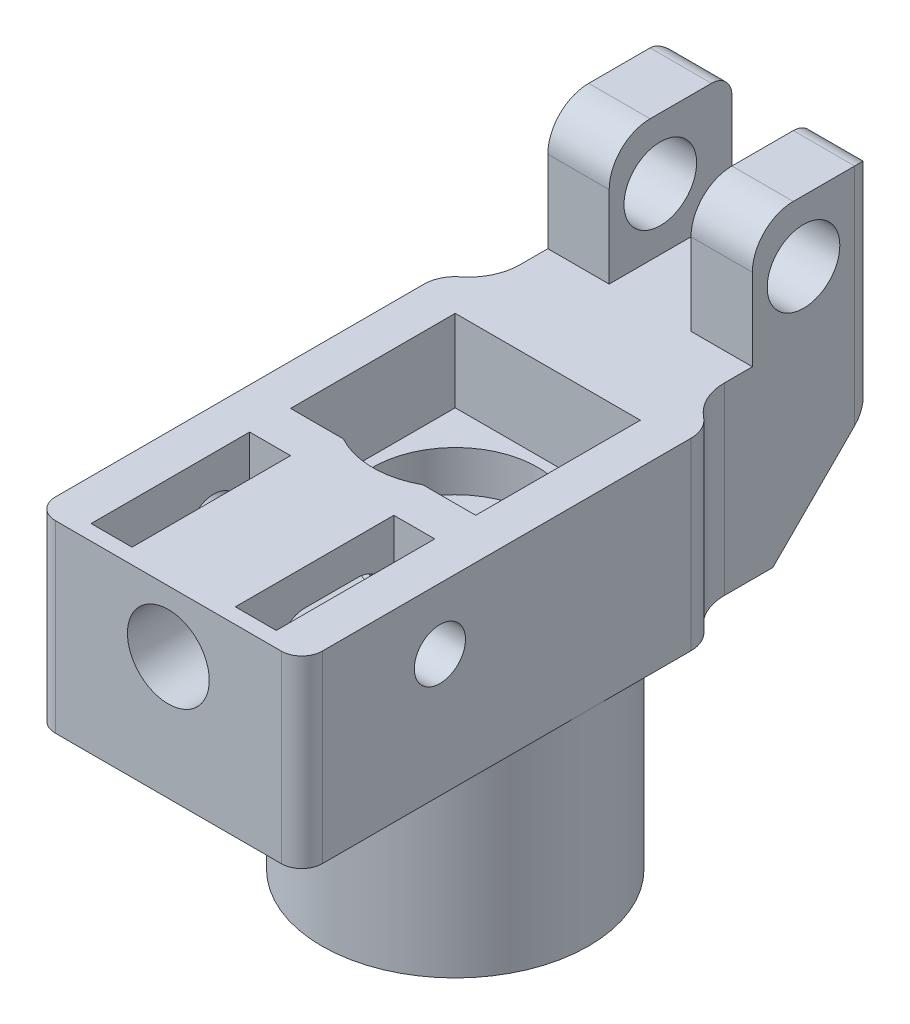
SolidWorks part; units mm, degrees
material "PF"
ref_plane "Front Plane" through (0, 0, 0) normal (0, 0, 1) x (1, 0, 0)
ref_plane "Top Plane" through (0, 0, 0) normal (0, 1, 0) x (1, 0, 0)
ref_plane "Right Plane" through (0, 0, 0) normal (1, 0, 0) x (0, 0, -1)
sketch "Sketch1" plane through (0, 0, 0) normal (0, 1, 0) x (1, 0, 0)
  circle A0 centre (0, 0) radius 8.05
  circle A1 centre (0, 0) radius 13.05
  dimension "D1" = 16.1
  dimension "D2" = 5
extrude "Boss-Extrude1" add sketch "Sketch1" along normal blind 20
sketch "Sketch2" plane through (0, 20, 0) normal (0, 1, 0) x (1, 0, 0)
  line L2 (-13.05, -13.05) -> (-13.05, 10)
  line L3 (-10, 13.05) -> (10, 13.05)
  line L4 (13.05, -13.05) -> (13.05, 10)
  line L6 (-13.05, -13.05) -> (-13.05, -28.05)
  line L7 (-13.05, -28.05) -> (13.05, -28.05)
  line L8 (13.05, -13.05) -> (13.05, -28.05)
  circle A0 centre (0, 0) radius 8.05
  arc A1 (10, 13.05) -> (13.05, 10) centre (10, 10) cw
  arc A2 (-13.05, 10) -> (-10, 13.05) centre (-10, 10) cw
  point P0 (0, 0)
  dimension "D2" = 3.05
  dimension "D1" = 15
extrude "Boss-Extrude2" add sketch "Sketch2" along normal blind 10
sketch "Sketch3" plane through (0, 30, 0) normal (0, 1, 0) x (1, 0, 0)
  line L5 (9.05, -11.05) -> (-9.05, -11.05)
  line L6 (-9.05, -11.05) -> (-9.05, -24.05)
  line L8 (-9.05, 9.05) -> (-9.05, -24.05)
  line L9 (-9.05, -24.05) -> (9.05, -24.05)
  line L10 (9.05, -24.05) -> (9.05, 9.05)
  line L11 (9.05, 9.05) -> (-9.05, 9.05)
  line L13 (-9.05, -24.05) -> (9.05, -24.05)
  line L14 (9.05, -24.05) -> (9.05, -11.05)
  dimension "D1" = 4
extrude "Cut-Extrude1" cut sketch "Sketch3" against normal blind 4
sketch "Sketch4" plane through (0, 30, 0) normal (0, 1, 0) x (1, 0, 0)
  line L8 (-9.05, 9.05) -> (-9.05, -24.05)
  line L9 (-9.05, -24.05) -> (9.05, -24.05)
  line L10 (9.05, -24.05) -> (9.05, 9.05)
  line L11 (9.05, 9.05) -> (-9.05, 9.05)
  line L12 (-9.05, 9.05) -> (-9.05, -7.05)
  line L13 (-9.05, -24.05) -> (9.05, -24.05)
  line L14 (9.05, -24.05) -> (9.05, -11.05)
  line L15 (9.05, 9.05) -> (-9.05, 9.05)
  line L25 (-9.05, -11.05) -> (9.05, -11.05)
  line L26 (-9.05, -7.05) -> (-3.8859, -7.05)
  line L27 (3.8859, -7.05) -> (9.05, -7.05)
  line L28 (-9.05, -7.05) -> (9.05, -7.05) construction
  line L29 (-13.05, -28.05) -> (13.05, -28.05)
  line L30 (13.05, -28.05) -> (13.05, 10)
  line L31 (10, 13.05) -> (-10, 13.05)
  line L32 (-13.05, 10) -> (-13.05, -28.05)
  line L33 (-13.05, -28.05) -> (13.05, -28.05)
  line L34 (13.05, -28.05) -> (13.05, 10)
  line L35 (10, 13.05) -> (-10, 13.05)
  line L36 (-13.05, 10) -> (-13.05, -28.05)
  line L37 (-9.05, -11.05) -> (-9.05, -24.05)
  line L38 (9.05, -7.05) -> (9.05, 9.05)
  arc A10 (-3.8859, -7.05) -> (3.8859, -7.05) centre (0, 0) ccw
  arc A12 (13.05, 10) -> (10, 13.05) centre (10, 10) ccw
  arc A13 (-10, 13.05) -> (-13.05, 10) centre (-10, 10) ccw
  arc A14 (13.05, 10) -> (10, 13.05) centre (10, 10) ccw
  arc A15 (-10, 13.05) -> (-13.05, 10) centre (-10, 10) ccw
  dimension "D1" = 4
  dimension "D2" = 0
  dimension "D3" = 4
extrude "Boss-Extrude3" add sketch "Sketch4" along normal blind 8
ref_plane "Plane1" through (0, 20, 0) normal (0, 1, 0) x (1, 0, 0)
sketch "Sketch5" plane through (0, 20, 0) normal (0, 1, 0) x (1, 0, 0)
  circle A0 centre (0, 0) radius 4
  circle A1 centre (0, 0) radius 8.05
  dimension "D1" = 8
extrude "Boss-Extrude4" add sketch "Sketch5" along normal blind 6
sketch "Sketch10" plane through (0, 26, 0) normal (0, 1, 0) x (1, 0, 0)
  line L0 (-9.05, -24.05) -> (9.05, -24.05) construction
  line L1 (-5.05, -24.05) -> (5.05, -24.05)
  line L2 (-5.05, -24.05) -> (-5.05, -11.05)
  line L3 (-5.05, -11.05) -> (5.05, -11.05)
  line L4 (5.05, -24.05) -> (5.05, -11.05)
  line L5 (-9.05, -11.05) -> (-9.05, -24.05) construction
  line L6 (9.05, -24.05) -> (9.05, -11.05) construction
  line L7 (9.05, -11.05) -> (-9.05, -11.05) construction
  dimension "D1" = 4
  dimension "D2" = 4
  dimension "D3" = 0
extrude "Boss-Extrude7" add sketch "Sketch10" along normal up to surface (12 mm away) up to face at (0, 38, 1.4561)
sketch "Sketch6" plane through (0, 0, 28.05) normal (0, 0, 1) x (1, 0, 0)
  line L0 (-13.05, 38) -> (13.05, 38) construction
  circle A0 centre (0, 32) radius 4
  dimension "D1" = 8
  dimension "D2" = 6
extrude "Cut-Extrude2" cut sketch "Sketch6" against normal up to surface (21 mm away) up to face at (-6.4679, 34, 7.05)
sketch "Sketch7" plane through (13.05, 0, 0) normal (1, 0, 0) x (0, 0, -1)
  line L0 (-28.05, 38) -> (10, 38) construction
  line L1 (-11.05, 26) -> (-11.05, 38) construction
  circle A0 centre (-14.55, 32) radius 2.5
  dimension "D1" = 6
  dimension "D2" = 3.5
extrude "Cut-Extrude3" cut sketch "Sketch7" against normal through all both and the other way through all
sketch "Sketch8" plane through (0, 0, 0) normal (1, 0, 0) x (0, 0, -1)
  line L0 (21.05, 20) -> (31.05, 30)
  line L1 (13.05, 38) -> (31.05, 38)
  line L2 (13.05, 38) -> (13.05, 20)
  line L3 (13.05, 20) -> (21.05, 20)
  line L4 (31.05, 38) -> (31.05, 30)
  point P1 (31.05, 20)
  dimension "D1" = 18
extrude "Boss-Extrude5" add sketch "Sketch8" along normal mid plane 20
sketch "Sketch13" plane through (0, 38, 0) normal (0, 1, 0) x (1, 0, 0)
  line L0 (10, 31.05) -> (10, 13.05) construction
  line L1 (-10, 31.05) -> (-4, 31.05)
  line L2 (-10, 31.05) -> (-10, 19.05)
  line L3 (-10, 19.05) -> (-4, 19.05)
  line L4 (10, 31.05) -> (10, 19.05)
  line L5 (4, 19.05) -> (10, 19.05)
  line L7 (-4, 31.05) -> (-4, 19.05)
  line L9 (4, 31.05) -> (4, 19.05)
  line L10 (4, 31.05) -> (10, 31.05)
  dimension "D1" = 12
  dimension "D2" = 6
  dimension "D3" = 6
extrude "Boss-Extrude8" add sketch "Sketch13" along normal blind 12
fillet "Fillet1" radius 5 2 edges at (-10, 29, -13.05) (10, 29, -13.05)
fillet "Fillet2" radius 2 4 edges at (-10, 40, -31.05) (10, 40, -31.05) (-7, 50, -31.05) (7, 50, -31.05)
sketch "Sketch11" plane through (5.05, 0, 0) normal (1, 0, 0) x (0, 0, -1)
  line L1 (-19.75, 29.5) -> (-14.55, 29.5)
  line L2 (-19.75, 34.5) -> (-14.55, 34.5)
  arc A0 (-19.75, 34.5) -> (-19.75, 29.5) centre (-19.75, 32) ccw
  circle A1 centre (-14.55, 32) radius 2.5 construction
  arc A2 (-14.55, 29.5) -> (-14.55, 34.5) centre (-14.55, 32) ccw
  dimension "D1" = 5
  dimension "D2" = 5.2
extrude "Cut-Extrude4" cut sketch "Sketch11" against normal up to surface (10.1 mm away) up to face at (-5.05, 32, 12.05)
sketch "Sketch14" plane through (10, 0, 0) normal (1, 0, 0) x (0, 0, -1)
  circle A0 centre (24.05, 44) radius 3.55
  dimension "D1" = 7.1
extrude "Cut-Extrude5" cut sketch "Sketch14" against normal up to surface (20 mm away) up to face at (-10, 34.8571, -21.4097)
fillet "Fillet4" radius 4 2 edges at (7, 50, -19.05) (-7, 50, -19.05)
fillet "Fillet5" radius 2 2 edges at (-13.05, 29, 28.05) (13.05, 29, 28.05)
sketch "Sketch15" plane through (0, 38, 0) normal (0, 1, 0) x (1, 0, 0)
  line L0 (0, -28.05) -> (0, -12.6679) construction
  line L1 (5.05, -24.05) -> (9.05, -24.05)
  line L2 (5.05, -24.05) -> (5.05, -26.55)
  line L3 (5.05, -26.55) -> (9.05, -26.55)
  line L4 (9.05, -24.05) -> (9.05, -26.55)
  line L5 (-11.05, -28.05) -> (11.05, -28.05) construction
  line L6 (-9.05, -24.05) -> (-9.05, -26.55)
  line L7 (-5.05, -26.55) -> (-9.05, -26.55)
  line L8 (-5.05, -24.05) -> (-5.05, -26.55)
  line L9 (-5.05, -24.05) -> (-9.05, -24.05)
  dimension "D1" = 2.5
extrude "Cut-Extrude6" cut sketch "Sketch15" against normal up to surface (12 mm away) up to face at (-7.05, 26, 17.55)
